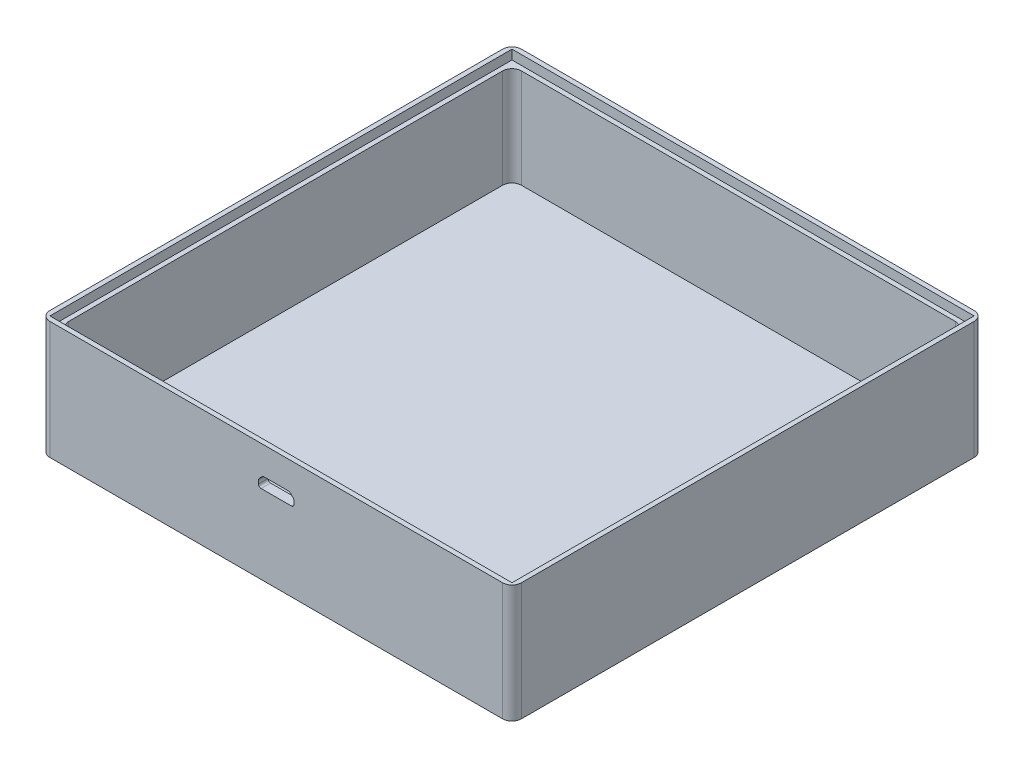
SolidWorks part; units mm, degrees
ref_plane "Front Plane" through (0, 0, 0) normal (0, 0, 1) x (1, 0, 0)
ref_plane "Top Plane" through (0, 0, 0) normal (0, 1, 0) x (1, 0, 0)
ref_plane "Right Plane" through (0, 0, 0) normal (1, 0, 0) x (0, 0, -1)
sketch "Sketch1" plane through (0, 0, 0) normal (0, 1, 0) x (1, 0, 0)
  line L0 (-50, 50) -> (0, 0) construction
  line L1 (0, -50) -> (50, -50)
  line L2 (50, -50) -> (50, 50)
  line L4 (-50, 50) -> (-50, -50)
  line L5 (-50, -50) -> (0, -50)
  line L6 (-50, 50) -> (50, 50)
  line L7 (-50, -50) -> (0, 0) construction
  line L8 (0, 0) -> (50, 50) construction
  line L9 (0, 0) -> (50, -50) construction
  dimension "D1" = 100
  dimension "D3" = 100
  dimension "D4" = 50
extrude "Boss-Extrude1" add sketch "Sketch1" along normal blind 25
shell "Shell8" thickness 2
sketch "Sketch2" plane through (0, 0, 0) normal (0, 0, 1) x (1, 0, 0)
  line L0 (0, 25) -> (0, 21)
  line L1 (-50, 25) -> (50, 25) construction
  line L3 (0, 21) -> (0, 19.4)
  line L4 (0, 21) -> (-48, 21)
  line L7 (48, 21) -> (48, 2)
  line L8 (48, 2) -> (-48, 2)
  line L9 (-48, 2) -> (-48, 21)
  line L10 (0, 21) -> (48, 21)
  line L18 (-3.75, 17.255) -> (-3.75, 18.0014)
  line L19 (-3.5889, 18.3904) -> (-2.9854, 18.9939)
  line L20 (2.5964, 19.155) -> (-2.5964, 19.155)
  line L21 (3.5889, 18.3904) -> (2.9854, 18.9939)
  line L22 (3.2, 16.705) -> (-3.2, 16.705)
  line L23 (3.75, 17.255) -> (3.75, 18.0014)
  arc A6 (-3.75, 17.255) -> (-3.2, 16.705) centre (-3.2, 17.255) ccw
  arc A7 (-2.5964, 19.155) -> (-2.9854, 18.9939) centre (-2.5964, 18.605) ccw
  arc A8 (-3.5889, 18.3904) -> (-3.75, 18.0014) centre (-3.2, 18.0014) ccw
  arc A9 (3.5889, 18.3904) -> (3.75, 18.0014) centre (3.2, 18.0014) cw
  arc A10 (2.5964, 19.155) -> (2.9854, 18.9939) centre (2.5964, 18.605) cw
  arc A11 (3.75, 17.255) -> (3.2, 16.705) centre (3.2, 17.255) cw
extrude "Cut-Extrude1" cut sketch "Sketch2" along normal through all contours A11 L23 A9 L21 A10 L20 A7 L19 A8 L18 A6 L22
sketch "Sketch3" plane through (0, 25, 0) normal (0, 1, 0) x (1, 0, 0)
  line L3 (-49, -49) -> (-49, 49)
  line L4 (-49, 49) -> (49, 49)
  line L5 (49, 49) -> (49, -49)
  line L6 (49, -49) -> (-49, -49)
extrude "Cut-Extrude2" cut sketch "Sketch3" against normal blind 2
fillet "Fillet1" radius 2 4 edges at (-50, 12.5, 50) (-50, 12.5, -50) (50, 12.5, -50) (50, 12.5, 50)
fillet "Fillet2" radius 2 4 edges at (48, 12.5, 48) (48, 12.5, -48) (-48, 12.5, -48) (-48, 12.5, 48)
